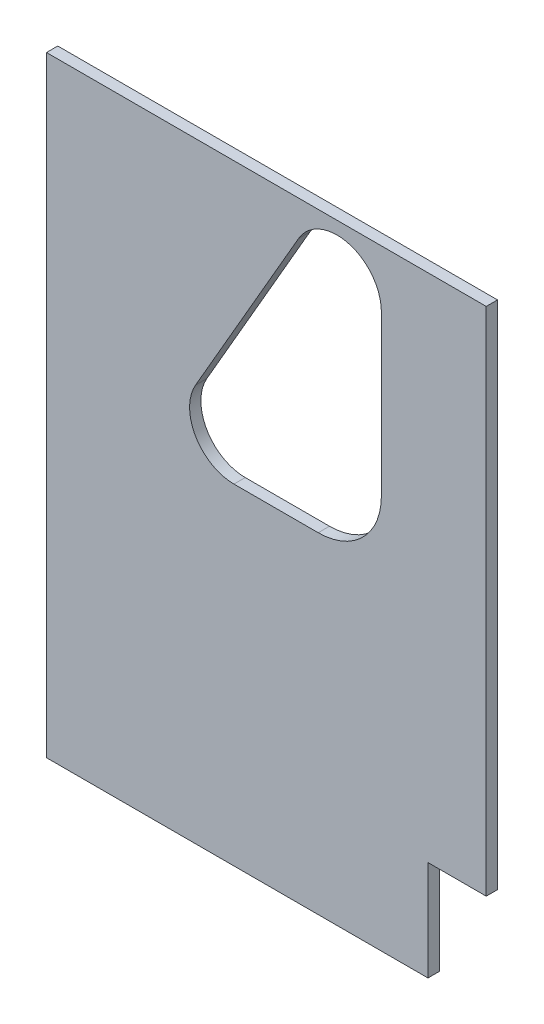
SolidWorks part; units mm, degrees
ref_plane "Front Plane" through (0, 0, 0) normal (0, 0, 1) x (1, 0, 0)
ref_plane "Top Plane" through (0, 0, 0) normal (0, 1, 0) x (1, 0, 0)
ref_plane "Right Plane" through (0, 0, 0) normal (1, 0, 0) x (0, 0, -1)
sketch "Sketch1" plane through (0, 0, 0) normal (0, 0, 1) x (1, 0, 0)
  line L1 (0, 0) -> (1015, 0)
  line L2 (0, 0) -> (0, 1625)
  line L3 (0, 1625) -> (1170, 1625)
  line L4 (1170, 266) -> (1170, 1625)
  line L5 (1170, 266) -> (1015, 266)
  line L8 (1015, 266) -> (1015, 0)
  dimension "D1" = 1170
  dimension "D2" = 1625
  dimension "D3" = 155
  dimension "D4" = 266
extrude "Boss-Extrude1" add sketch "Sketch1" along normal blind 30
extrude "Cut-Extrude1" cut sketch "Sketch2" against normal through all
sketch "Sketch2" plane through (-119.4366, -43.0714, 31) normal (0, 0, 1) x (1, 0, 0)
  line L0 (1010.4366, 1516.0714) -> (1010.4366, 1091.0714)
  line L1 (842.4366, 923.0714) -> (618.1953, 923.0714)
  line L2 (516.0043, 1100.0714) -> (790.2456, 1575.0714)
  arc A0 (1010.4366, 1091.0714) -> (842.4366, 923.0714) centre (842.4366, 1091.0714) cw
  arc A1 (618.1953, 923.0714) -> (516.0043, 1100.0714) centre (618.1953, 1041.0714) cw
  arc A2 (1010.4366, 1516.0714) -> (790.2456, 1575.0714) centre (892.4366, 1516.0714) ccw
  point P5 (799.5237, 866.5543)
  point P6 (321.2838, 682.0482)
  point P7 (955.4941, 1600.8385)
  point P12 (750.0994, 693.895)
